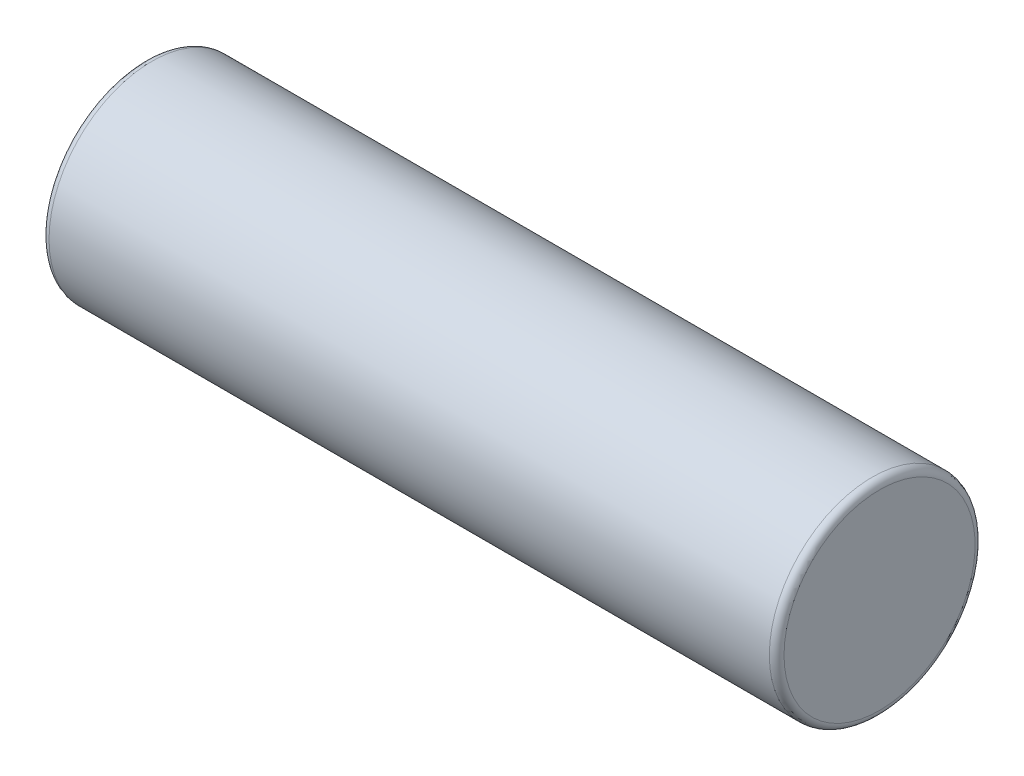
SolidWorks part; units mm, degrees
ref_plane "Спереди" through (0, 0, 0) normal (0, 0, 1) x (1, 0, 0)
ref_plane "Сверху" through (0, 0, 0) normal (0, 1, 0) x (1, 0, 0)
ref_plane "Справа" through (0, 0, 0) normal (1, 0, 0) x (0, 0, -1)
sketch "Эскиз1" plane through (0, 0, 0) normal (0, 0, 1) x (1, 0, 0)
  line L0 (0, 0) -> (22.5241, 0) construction
  line L1 (0, 0) -> (0, 7)
  line L2 (0, 7) -> (50, 7)
  line L3 (50, 7) -> (50, 0)
  line L4 (50, 0) -> (0, 0)
  dimension "D1" = 14
  dimension "D2" = 50
revolve "Повернуть1" add sketch "Эскиз1" angle 360 about L0
fillet "Скругление1" radius 0.5 2 edges at (50, 0, 7) (0, 0, 7)
